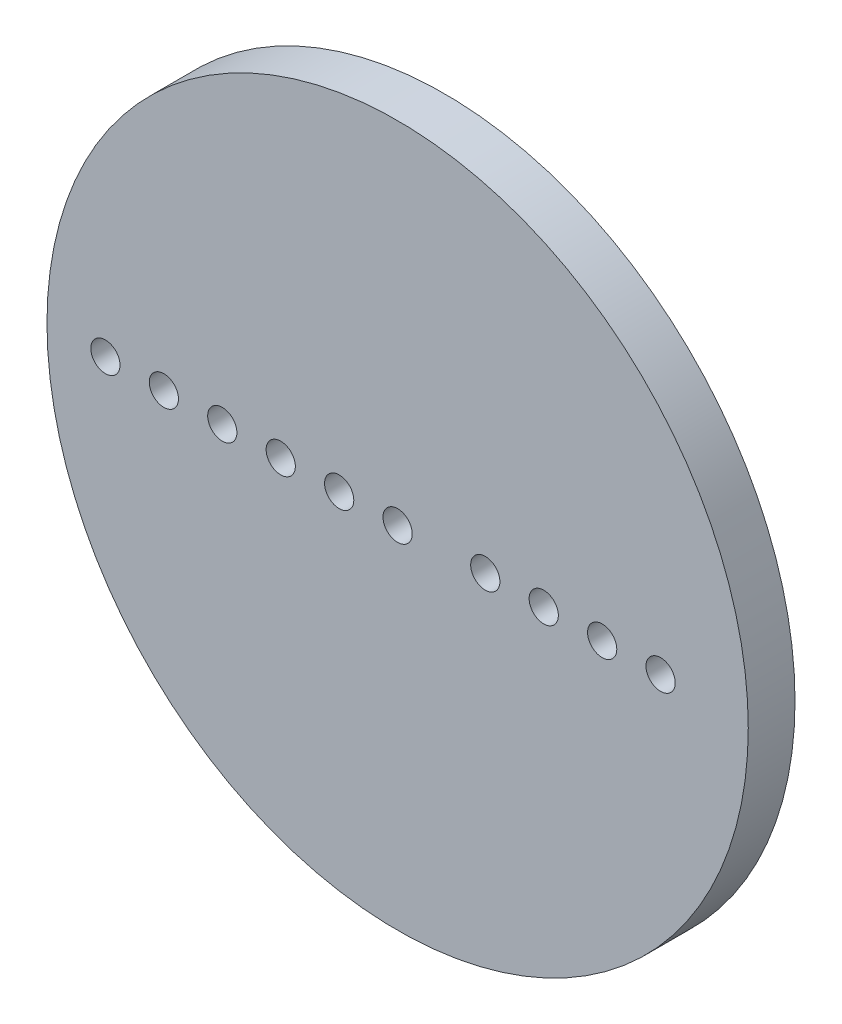
SolidWorks part; units mm, degrees
ref_plane "Front Plane" through (0, 0, 0) normal (0, 0, 1) x (1, 0, 0)
ref_plane "Top Plane" through (0, 0, 0) normal (0, 1, 0) x (1, 0, 0)
ref_plane "Right Plane" through (0, 0, 0) normal (1, 0, 0) x (0, 0, -1)
sketch "Sketch1" plane through (0, 0, 0) normal (0, 0, 1) x (1, 0, 0)
  circle A0 centre (0, 0) radius 60
  circle A1 centre (0, 0) radius 2.5
  circle A2 centre (-10, 0) radius 2.5
  circle A3 centre (-20, 0) radius 2.5
  circle A4 centre (-30, 0) radius 2.5
  circle A5 centre (-40, 0) radius 2.5
  circle A6 centre (-50, 0) radius 2.5
  circle A8 centre (45, 0.4194) radius 2.5
  circle A9 centre (35, 0.4194) radius 2.5
  circle A10 centre (25, 0.4194) radius 2.5
  circle A11 centre (15, 0.4194) radius 2.5
  dimension "D1" = 120
  dimension "D2" = 5
  dimension "D4" = 10
  dimension "D3" = 10
  dimension "D12" = 15
extrude "Boss-Extrude1" add sketch "Sketch1" along normal mid plane 8
sketch "Sketch2" plane through (0, 0, 4) normal (0, 0, 1) x (1, 0, 0)
